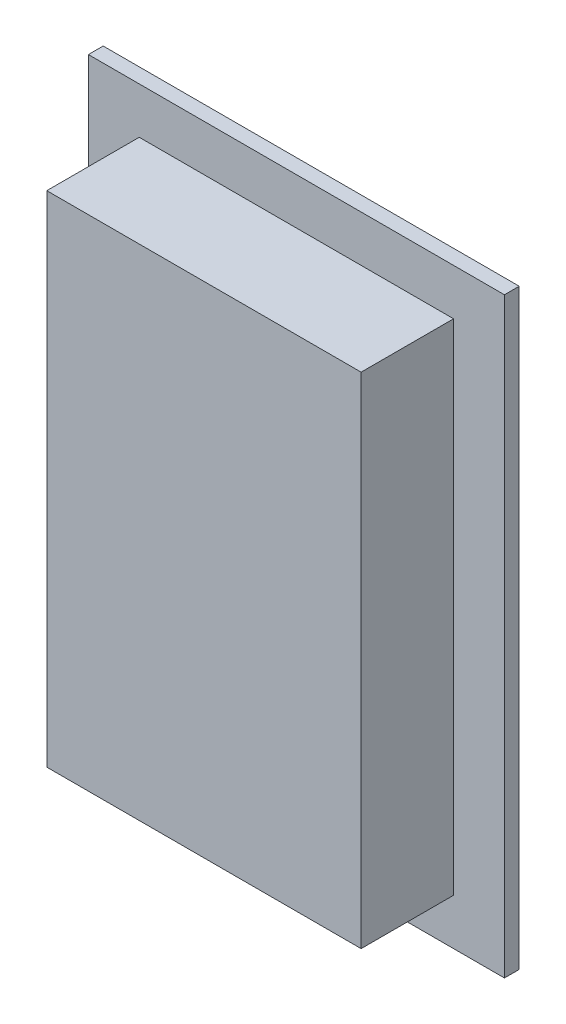
SolidWorks part; units mm, degrees
material "ABS"
ref_plane "Front Plane" through (0, 0, 0) normal (0, 0, 1) x (1, 0, 0)
ref_plane "Top Plane" through (0, 0, 0) normal (0, 1, 0) x (1, 0, 0)
ref_plane "Right Plane" through (0, 0, 0) normal (1, 0, 0) x (0, 0, -1)
sketch "Sketch1" plane through (0, 0, 0) normal (0, 0, 1) x (1, 0, 0)
  line L1 (-97.5, -32) -> (-52.5, -32)
  line L2 (-97.5, -32) -> (-97.5, 32)
  line L3 (-97.5, 32) -> (-52.5, 32)
  line L4 (-52.5, -32) -> (-52.5, 32)
extrude "Boss-Extrude1" add sketch "Sketch1" along normal mid plane 1.6 from offset 18.4
sketch "Sketch2" plane through (0, 0, 0) normal (0, 0, 1) x (1, 0, 0)
  line L1 (-92, -27) -> (-58, -27)
  line L2 (-92, -27) -> (-92, 27)
  line L3 (-92, 27) -> (-58, 27)
  line L4 (-58, -27) -> (-58, 27)
extrude "Boss-Extrude2" add sketch "Sketch2" along normal mid plane 10 from offset 24.2
